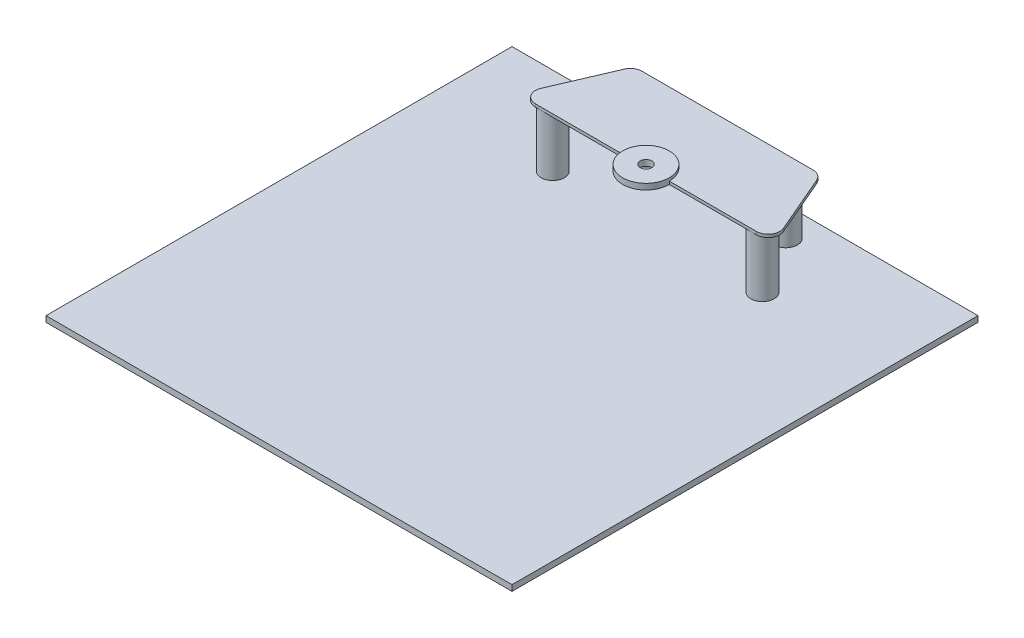
SolidWorks part; units mm, degrees
ref_plane "Front Plane" through (0, 0, 0) normal (0, 0, 1) x (1, 0, 0)
ref_plane "Top Plane" through (0, 0, 0) normal (0, 1, 0) x (1, 0, 0)
ref_plane "Right Plane" through (0, 0, 0) normal (1, 0, 0) x (0, 0, -1)
sketch "Sketch1" plane through (0, 0, 0) normal (0, 1, 0) x (1, 0, 0)
  line L1 (-400, -400) -> (400, -400)
  line L2 (-400, -400) -> (-400, 400)
  line L3 (-400, 400) -> (400, 400)
  line L4 (400, -400) -> (400, 400)
  line L5 (-400, -400) -> (400, 400) construction
  line L6 (-400, 400) -> (400, -400) construction
  point P0 (0, 0)
  dimension "D1" = 800
  dimension "D2" = 800
extrude "Boss-Extrude4" add sketch "Sketch1" along normal blind 10 contours L4 L3 L2 L1
sketch "Sketch6" plane through (0, 10, 0) normal (0, 1, 0) x (1, 0, 0)
  line L0 (0, 400) -> (120, 400) construction
  line L2 (-400, 400) -> (400, 400) construction
  line L3 (0, 400) -> (-120, 400) construction
  line L4 (120, 400) -> (120, 350) construction
  line L5 (-120, 400) -> (-120, 350) construction
  line L6 (0, 400) -> (-180, 400) construction
  line L7 (0, 400) -> (180, 400) construction
  line L8 (-180, 400) -> (-180, 250) construction
  line L9 (180, 400) -> (180, 250) construction
  circle A0 centre (120, 350) radius 20
  circle A1 centre (-120, 350) radius 20
  circle A2 centre (-180, 250) radius 20
  circle A3 centre (180, 250) radius 20
  dimension "D5" = 40
  dimension "D6" = 40
  dimension "D11" = 40
  dimension "D12" = 40
  dimension "D1" = 120
  dimension "D2" = 120
  dimension "D3" = 50
  dimension "D4" = 50
  dimension "D7" = 180
  dimension "D8" = 180
  dimension "D9" = 150
  dimension "D10" = 150
extrude "Boss-Extrude5" add sketch "Sketch6" along normal blind 100
sketch "Sketch7" plane through (0, 110, 0) normal (0, 1, 0) x (1, 0, 0)
  line L0 (-120, 370) -> (120, 370)
  line L1 (-180, 230) -> (180, 230)
  line L2 (189.6692, 230) -> (180, 230)
  line L3 (-180, 230) -> (-189.6692, 230)
  line L4 (-120, 370) -> (-146.8121, 370)
  line L5 (120, 370) -> (146.8121, 370)
  line L6 (-165.195, 357.8784) -> (-208.0521, 257.8784)
  line L7 (165.195, 357.8784) -> (208.0521, 257.8784)
  circle A2 centre (-120, 350) radius 20 construction
  circle A3 centre (-120, 350) radius 20 construction
  circle A4 centre (120, 350) radius 20 construction
  circle A5 centre (-180, 250) radius 20 construction
  circle A6 centre (-180, 250) radius 20 construction
  circle A7 centre (180, 250) radius 20 construction
  circle A8 centre (180, 250) radius 20 construction
  arc A13 (146.8121, 370) -> (165.195, 357.8784) centre (146.8121, 350) cw
  arc A14 (208.0521, 257.8784) -> (189.6692, 230) centre (189.6692, 250) cw
  arc A15 (-189.6692, 230) -> (-208.0521, 257.8784) centre (-189.6692, 250) cw
  arc A16 (-165.195, 357.8784) -> (-146.8121, 370) centre (-146.8121, 350) cw
  point P21 (160, 370)
  point P26 (220, 230)
  point P33 (-220, 230)
  point P36 (-160, 370)
  dimension "D1" = 40
  dimension "D5" = 20
  dimension "D2" = 40
  dimension "D3" = 40
  dimension "D4" = 40
extrude "Boss-Extrude6" add sketch "Sketch7" along normal blind 5
sketch "Sketch8" plane through (0, 115, 0) normal (0, 1, 0) x (1, 0, 0)
  line L0 (-189.6692, 230) -> (189.6692, 230) construction
  circle A0 centre (0, 230) radius 40
  point P4 (0, 0)
  dimension "D1" = 80
extrude "Boss-Extrude7" add sketch "Sketch8" along normal blind 5 and the other way blind 5
sketch "Sketch9" plane through (0, 120, 0) normal (0, 1, 0) x (1, 0, 0)
  circle A0 centre (0, 230) radius 10
  dimension "D1" = 20
extrude "Cut-Extrude1" cut sketch "Sketch9" against normal blind 24 and the other way blind 5
